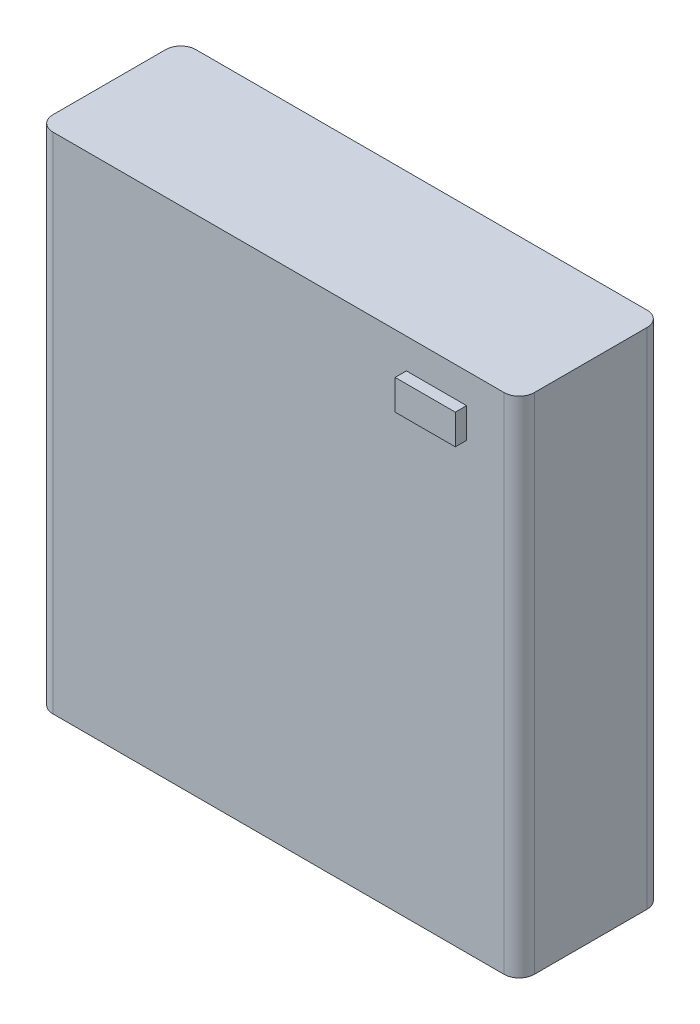
SolidWorks part; units mm, degrees
ref_plane "Front Plane" through (0, 0, 0) normal (0, 0, 1) x (1, 0, 0)
ref_plane "Top Plane" through (0, 0, 0) normal (0, 1, 0) x (1, 0, 0)
ref_plane "Right Plane" through (0, 0, 0) normal (1, 0, 0) x (0, 0, -1)
sketch "Sketch1" plane through (0, 0, 0) normal (0, 0, 1) x (1, 0, 0)
  line L1 (32, 33.5) -> (-32, 33.5)
  line L2 (32, 33.5) -> (32, -33.5)
  line L3 (32, -33.5) -> (-32, -33.5)
  line L4 (-32, 33.5) -> (-32, -33.5)
  line L5 (32, 33.5) -> (-32, -33.5) construction
  line L6 (32, -33.5) -> (-32, 33.5) construction
  point P0 (0, 0)
  dimension "D1" = 67
  dimension "D2" = 64
extrude "Boss-Extrude1" add sketch "Sketch1" along normal blind 19
sketch "Sketch2" plane through (0, 0, 19) normal (0, 0, 1) x (1, 0, 0)
  line L0 (32, -33.5) -> (32, 33.5) construction
  line L1 (17, 29.5) -> (25, 29.5)
  line L2 (17, 29.5) -> (17, 25.5)
  line L3 (17, 25.5) -> (25, 25.5)
  line L4 (25, 29.5) -> (25, 25.5)
  line L5 (32, 33.5) -> (-32, 33.5) construction
  dimension "D1" = 8
  dimension "D2" = 4
  dimension "D3" = 7
  dimension "D4" = 4
extrude "Boss-Extrude2" add sketch "Sketch2" along normal blind 1.5
fillet "Fillet1" radius 2 4 edges at (32, 0, 0) (32, 0, 19) (-32, 0, 0) (-32, 0, 19)
